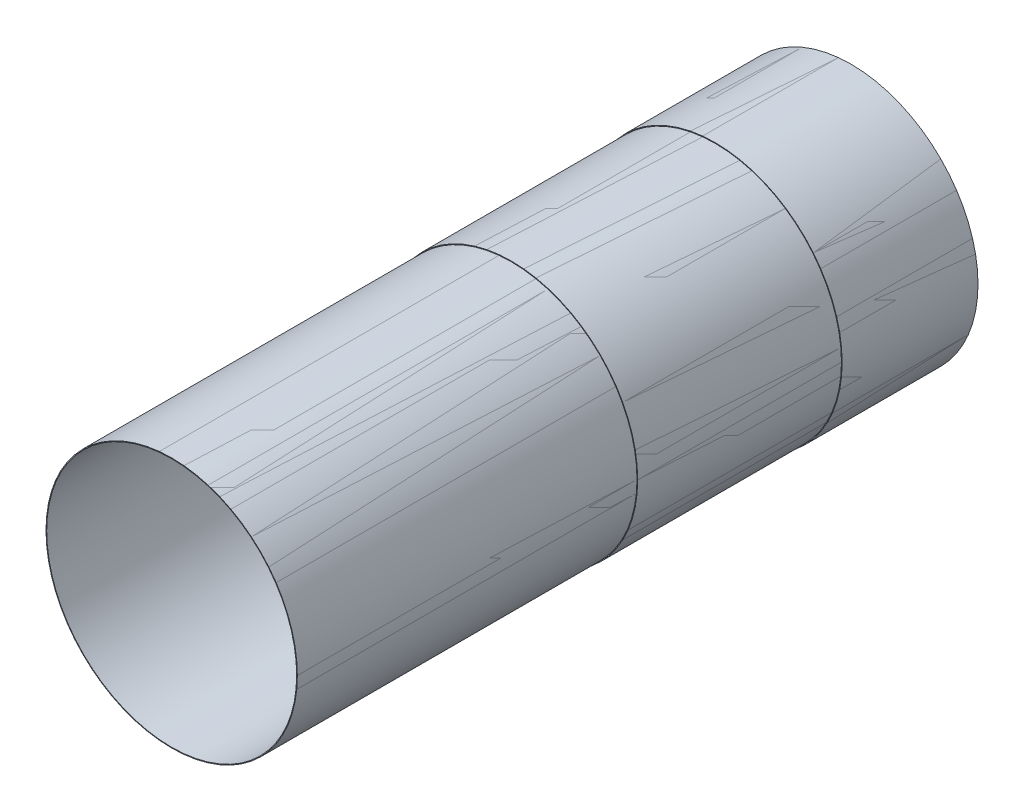
SolidWorks part; units mm, degrees
ref_plane "Front Plane" through (0, 0, 0) normal (0, 0, 1) x (1, 0, 0)
ref_plane "Top Plane" through (0, 0, 0) normal (0, 1, 0) x (1, 0, 0)
ref_plane "Right Plane" through (0, 0, 0) normal (1, 0, 0) x (0, 0, -1)
sketch "Sketch2" plane through (0, 0, 0) normal (0, 0, 1) x (1, 0, 0)
  circle A0 centre (0, 0) radius 184
  dimension "D1" = 368
extrude "Extrude-Thin1" add sketch "Sketch2" along normal blind 200 thin
sketch "Sketch3" plane through (0, 0, 200) normal (0, 0, 1) x (1, 0, 0)
  circle A0 centre (0, 0) radius 184 construction
  circle A1 centre (0, 0) radius 184
extrude "Extrude-Thin2" add sketch "Sketch3" along normal blind 300 separate body thin
sketch "Sketch4" plane through (0, 0, 500) normal (0, 0, 1) x (1, 0, 0)
  circle A0 centre (0, 0) radius 184 construction
  circle A1 centre (0, 0) radius 184
extrude "Extrude-Thin3" add sketch "Sketch4" along normal blind 500 separate body thin
surface "Surface-Offset1" parameters "D1"=0
